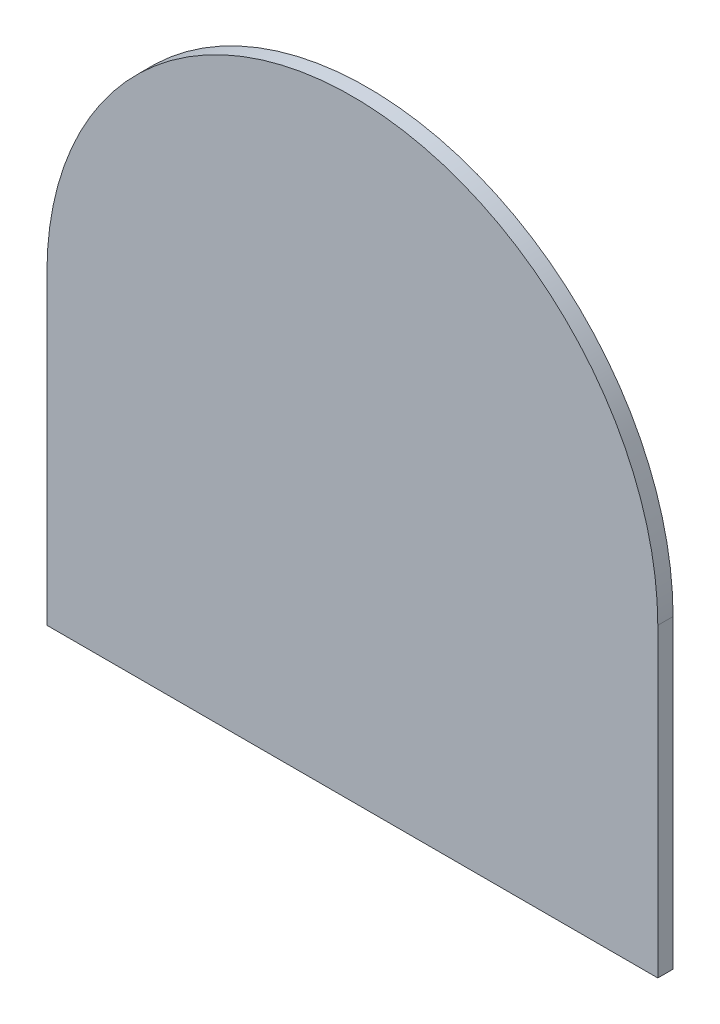
SolidWorks part; units mm, degrees
ref_plane "Front Plane" through (0, 0, 0) normal (0, 0, 1) x (1, 0, 0)
ref_plane "Top Plane" through (0, 0, 0) normal (0, 1, 0) x (1, 0, 0)
ref_plane "Right Plane" through (0, 0, 0) normal (1, 0, 0) x (0, 0, -1)
sketch "Sketch1" plane through (0, 0, 0) normal (0, 0, 1) x (1, 0, 0)
  line L1 (0, 0) -> (127, 0)
  line L2 (0, 0) -> (0, 63.5)
  line L4 (127, 0) -> (127, 63.5)
  arc A0 (127, 63.5) -> (0, 63.5) centre (63.5, 63.5) ccw
  dimension "D1" = 127
  dimension "D2" = 63.5
extrude "Extrude1" add sketch "Sketch1" against normal blind 3.175
sketch "Sketch2" plane through (0, 0, 0) normal (0, 0, 1) x (1, 0, 0)
  line L0 (89.6981, 49.9285) -> (105.5947, 49.9285)
  line L2 (89.6981, 86.8635) -> (89.6981, 79.8201)
  line L3 (21.4053, 49.9285) -> (37.3019, 49.9285)
  line L4 (21.4053, 49.9285) -> (21.4053, 79.8201)
  line L5 (21.4053, 79.8201) -> (37.3019, 79.8201)
  line L6 (105.5947, 49.9285) -> (105.5947, 79.8201)
  line L9 (37.3019, 86.8635) -> (37.3019, 79.8201)
  line L11 (89.6981, 79.8201) -> (105.5947, 79.8201)
  line L12 (37.3019, 42.8851) -> (37.3019, 49.9285)
  line L13 (89.6981, 42.8851) -> (89.6981, 49.9285)
  arc A0 (89.6981, 86.8635) -> (37.3019, 86.8635) centre (63.5, 60.6655) ccw
  arc A1 (89.6981, 42.8851) -> (37.3019, 42.8851) centre (63.5, 69.0832) cw
